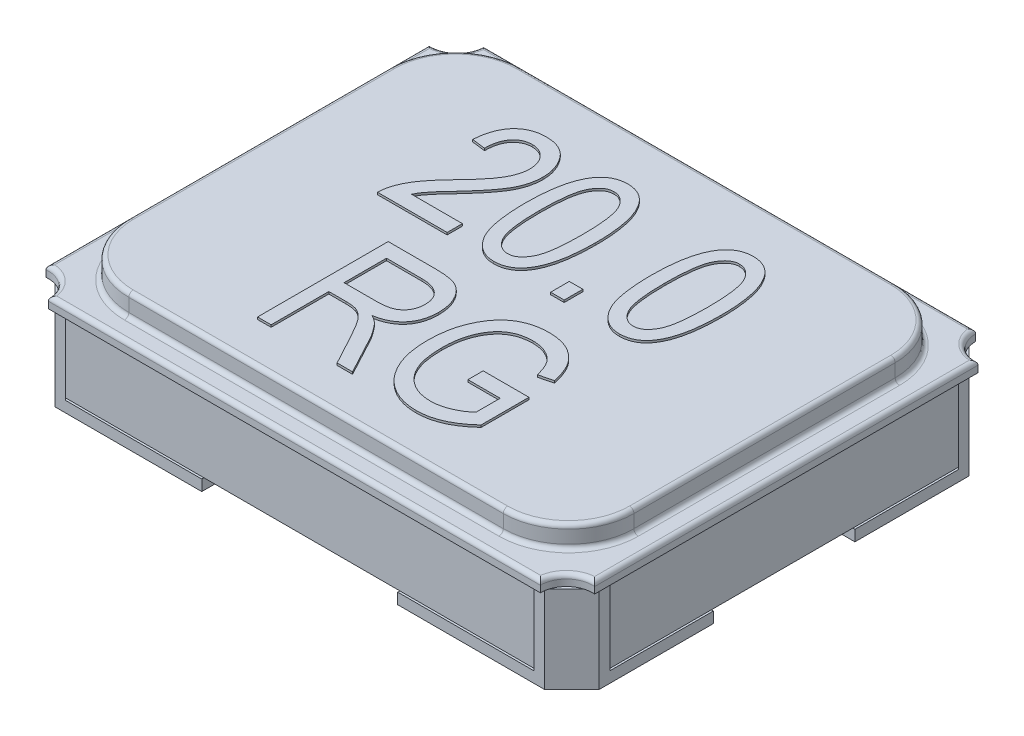
SolidWorks part; units mm, degrees
ref_plane "Спереди" through (0, 0, 0) normal (0, 0, 1) x (1, 0, 0)
ref_plane "Сверху" through (0, 0, 0) normal (0, 1, 0) x (1, 0, 0)
ref_plane "Справа" through (0, 0, 0) normal (1, 0, 0) x (0, 0, -1)
sketch "Эскиз2" plane through (0, 0, 0) normal (0, 1, 0) x (1, 0, 0)
  line L0 (0, 2.0584) -> (0, -2.2706) construction
  line L1 (1.25, 0.325) -> (0.45, 0.325) construction
  line L2 (1.3, -1) -> (-1.3, -1) construction
  line L3 (1.3, -1) -> (1.3, 1) construction
  line L4 (1.3, 1) -> (-1.1, 1) construction
  line L5 (-1.3, -1) -> (-1.3, 0.8) construction
  line L6 (1.3, -1) -> (-1.3, 1) construction
  line L7 (1.3, 1) -> (-1.3, -1) construction
  line L8 (-1.25, 0.975) -> (-0.45, 0.975) construction
  line L9 (-1.25, 0.975) -> (-1.25, 0.325) construction
  line L10 (-1.25, 0.325) -> (-0.45, 0.325) construction
  line L11 (-0.45, 0.975) -> (-0.45, 0.325) construction
  line L12 (-1.25, 0.975) -> (-0.45, 0.325) construction
  line L13 (2.9957, 0) -> (-3.2489, 0) construction
  line L14 (-1.25, 0.325) -> (-0.45, 0.975) construction
  line L15 (0.45, 0.975) -> (0.45, 0.325) construction
  line L16 (1.25, 0.975) -> (0.45, 0.975) construction
  line L17 (1.25, 0.975) -> (1.25, 0.325) construction
  line L18 (1.25, 0.325) -> (0.45, 0.975) construction
  line L19 (1.25, 0.975) -> (0.45, 0.325) construction
  line L20 (1.25, -0.975) -> (0.45, -0.325) construction
  line L21 (1.25, -0.325) -> (0.45, -0.975) construction
  line L22 (1.25, -0.975) -> (1.25, -0.325) construction
  line L23 (1.25, -0.975) -> (0.45, -0.975) construction
  line L24 (0.45, -0.975) -> (0.45, -0.325) construction
  line L25 (-1.25, -0.325) -> (-0.45, -0.975) construction
  line L26 (-1.25, -0.975) -> (-0.45, -0.325) construction
  line L27 (-0.45, -0.975) -> (-0.45, -0.325) construction
  line L28 (-1.25, -0.325) -> (-0.45, -0.325) construction
  line L29 (-1.25, -0.975) -> (-1.25, -0.325) construction
  line L30 (-1.25, -0.975) -> (-0.45, -0.975) construction
  line L31 (1.25, -0.325) -> (0.45, -0.325) construction
  line L32 (-1.1, 1) -> (-1.3, 0.8) construction
  line L33 (-1.25, 0.325) -> (-0.45, 0.325)
  line L34 (-0.45, 0.325) -> (-0.45, 0.975)
  line L35 (-0.45, 0.975) -> (-1.125, 0.975)
  line L36 (-1.125, 0.975) -> (-1.25, 0.85)
  line L37 (-1.25, 0.85) -> (-1.25, 0.325)
  line L38 (0.45, 0.325) -> (0.45, 0.975)
  line L39 (1.25, 0.325) -> (0.45, 0.325)
  line L40 (1.25, 0.85) -> (1.25, 0.325)
  line L41 (1.125, 0.975) -> (1.25, 0.85)
  line L42 (0.45, 0.975) -> (1.125, 0.975)
  line L43 (-1.25, -0.85) -> (-1.25, -0.325)
  line L44 (-1.125, -0.975) -> (-1.25, -0.85)
  line L45 (-0.45, -0.975) -> (-1.125, -0.975)
  line L46 (1.25, -0.325) -> (0.45, -0.325)
  line L47 (1.25, -0.85) -> (1.25, -0.325)
  line L48 (1.125, -0.975) -> (1.25, -0.85)
  line L49 (0.45, -0.975) -> (1.125, -0.975)
  line L50 (0.45, -0.325) -> (0.45, -0.975)
  line L51 (-1.25, -0.325) -> (-0.734, -0.325)
  line L52 (-0.734, -0.325) -> (-0.45, -0.5558)
  line L53 (-0.45, -0.5558) -> (-0.45, -0.975)
  point P2 (0, 0)
  point P7 (-0.85, 0.65)
  point P19 (0.85, 0.65)
  point P28 (0.85, -0.65)
  point P29 (-0.85, -0.65)
  dimension "D8" = 45
  dimension "D1" = 2
  dimension "D2" = 2.6
  dimension "D3" = 1.3
  dimension "D4" = 1.7
  dimension "D5" = 0.65
  dimension "D6" = 0.8
  dimension "D7" = 0.2
  dimension "D9" = 0.516
extrude "Вытянуть2" add sketch "Эскиз2" along normal blind 0.05
ref_plane "Плоскость1" through (-0.45, 0.05, 0.975) normal (0, 1, 0) x (-1, 0, 0)
sketch "Эскиз3" plane through (-0.45, 0.05, 0.975) normal (0, 1, 0) x (-1, 0, 0)
  line L0 (0.8, -1.825) -> (0.675, -1.95)
  line L1 (0.675, -1.95) -> (0.625, -1.95)
  line L2 (0, -1.95) -> (0.675, -1.95) construction
  line L3 (0.625, -1.95) -> (0.8, -1.775)
  line L4 (0.8, -1.825) -> (0.8, -1.3) construction
  line L5 (1.1032, -0.975) -> (-1.8964, -0.975) construction
  line L6 (-0.45, 0.2875) -> (-0.45, -2.7218) construction
  line L7 (0.8, -1.775) -> (0.8, -1.825)
  line L8 (-1.7, -1.775) -> (-1.7, -1.825)
  line L9 (-1.525, -1.95) -> (-1.7, -1.775)
  line L10 (-1.575, -1.95) -> (-1.525, -1.95)
  line L11 (-1.7, -1.825) -> (-1.575, -1.95)
  line L12 (-1.7, -0.125) -> (-1.575, 0)
  line L13 (-1.575, 0) -> (-1.525, 0)
  line L14 (-1.525, 0) -> (-1.7, -0.175)
  line L15 (-1.7, -0.175) -> (-1.7, -0.125)
  line L16 (0.8, -0.175) -> (0.8, -0.125)
  line L17 (0.625, 0) -> (0.8, -0.175)
  line L18 (0.675, 0) -> (0.625, 0)
  line L19 (0.8, -0.125) -> (0.675, 0)
  dimension "D1" = 0.05
extrude "Вытянуть4" add sketch "Эскиз3" along normal blind 0.35
sketch "Эскиз4" plane through (-0.45, 0.05, 0.975) normal (0, 1, 0) x (-1, 0, 0)
  line L0 (-1.6905, -1.7845) -> (-1.5391, -1.9359)
  line L1 (-1.5391, -1.9359) -> (0.65, -1.925)
  line L2 (-1.525, -1.95) -> (-1.7, -1.775) construction
  line L4 (0.8, -1.775) -> (0.625, -1.95) construction
  line L5 (-1.6905, -1.7845) -> (-1.6905, -0.1655)
  line L7 (-1.7, -0.175) -> (-1.525, 0) construction
  line L8 (-1.6905, -0.1655) -> (-1.535, -0.01)
  line L10 (-1.535, -0.01) -> (0.635, -0.01)
  line L11 (0.625, 0) -> (0.8, -0.175) construction
  line L12 (0.635, -0.01) -> (0.79, -0.165)
  line L14 (0.79, -0.165) -> (0.79, -1.785)
  line L15 (1.0658, -0.975) -> (-2.5223, -0.975) construction
  line L16 (0.65, -1.925) -> (0.79, -1.785)
  dimension "D2" = 2.17
  dimension "D1" = 1.62
extrude "Вытянуть6" add sketch "Эскиз4" along normal blind 0.35
ref_plane "Плоскость2" through (0, 0.4, 0.965) normal (0, 1, 0) x (-1, 0, 0)
sketch "Эскиз5" plane through (0, 0.4, 0.965) normal (0, 1, 0) x (-1, 0, 0)
  line L0 (1.3441, -0.965) -> (-1.4137, -0.965) construction
  line L1 (1.13, 0.035) -> (-1.13, 0.035)
  line L2 (-1.26, -0.0846) -> (-1.26, -1.8454)
  line L3 (1.13, -1.965) -> (-1.13, -1.965)
  line L4 (1.26, -1.8454) -> (1.26, -0.0846)
  line L5 (-1.25, 0.035) -> (1.25, -1.965) construction
  line L6 (-1.25, -1.965) -> (1.25, 0.035) construction
  line L7 (0, -2.1539) -> (0, 0.2767) construction
  arc A0 (1.13, 0.035) -> (1.26, -0.0846) centre (1.25, 0.035) ccw
  arc A1 (-1.13, 0.035) -> (-1.26, -0.0846) centre (-1.25, 0.035) cw
  arc A2 (1.13, -1.965) -> (1.26, -1.8454) centre (1.25, -1.965) cw
  arc A3 (-1.13, -1.965) -> (-1.26, -1.8454) centre (-1.25, -1.965) ccw
  point P0 (0, -0.965)
  dimension "D3" = 0.12
  dimension "D1" = 2.52
  dimension "D2" = 2
extrude "Вытянуть9" add sketch "Эскиз5" along normal blind 0.05
sketch "Эскиз6" plane through (0, 0.45, 0) normal (0, 1, 0) x (1, 0, 0)
  line L1 (1.16, -0.9) -> (-1.16, -0.9)
  line L2 (1.16, -0.9) -> (1.16, 0.9)
  line L3 (1.16, 0.9) -> (-1.16, 0.9)
  line L4 (-1.16, -0.9) -> (-1.16, 0.9)
  line L5 (1.16, -0.9) -> (-1.16, 0.9) construction
  line L6 (1.16, 0.9) -> (-1.16, -0.9) construction
  point P0 (0, 0)
  dimension "D1" = 2.32
  dimension "D2" = 1.8
extrude "Вытянуть10" add sketch "Эскиз6" along normal blind 0.1
fillet "Скругление2" radius 0.3 4 edges at (1.16, 0.5, -0.9) (1.16, 0.5, 0.9) (-1.16, 0.5, -0.9) (-1.16, 0.5, 0.9)
fillet "Скругление3" radius 0.02 24 edges at (1.0721, 0.45, 0.8121) (1.16, 0.45, 0) (1.0721, 0.45, -0.8121) (0, 0.45, -0.9) (-1.0721, 0.45, -0.8121) (-1.16, 0.45, 0) (-1.0721, 0.45, 0.8121) (0, 0.45, 0.9) (1.0721, 0.55, 0.8121) (0, 0.55, 0.9) (-1.0721, 0.55, 0.8121) (-1.16, 0.55, 0) (-1.0721, 0.55, -0.8121) (0, 0.55, -0.9) (1.0721, 0.55, -0.8121) (1.16, 0.55, 0) (-1.26, 0.45, 0) (-1.1688, 0.45, -0.9117) (0, 0.45, -1) (1.1688, 0.45, -0.9117) (1.26, 0.45, 0) (1.1688, 0.45, 0.9117) (0, 0.45, 1) (-1.1688, 0.45, 0.9117)
sketch "Эскиз7" plane through (0, 0.55, 0) normal (0, 1, 0) x (-1, 0, 0)
  line L0 (0.708, -0.0594) -> (-1.0255, -0.0594) construction
  line L1 (0.5111, 0.7122) -> (-0.8354, 0.7122) construction
  text T0 "20.0" font "Arial Narrow" height 0.6
  text T1 "RG" font "Arial Narrow" height 0.6
extrude "Вытянуть11" add sketch "Эскиз7" along normal blind 0.01
